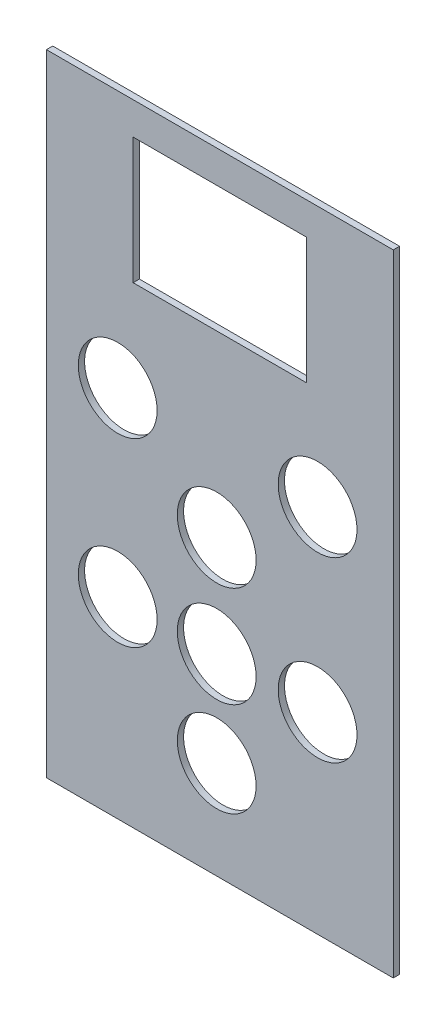
SolidWorks part; units mm, degrees
ref_plane "前视基准面" through (0, 0, 0) normal (0, 0, 1) x (1, 0, 0)
ref_plane "上视基准面" through (0, 0, 0) normal (0, 1, 0) x (1, 0, 0)
ref_plane "右视基准面" through (0, 0, 0) normal (1, 0, 0) x (0, 0, -1)
sketch "草图1" plane through (0, 0, 0) normal (0, 0, 1) x (1, 0, 0)
  line L0 (51.6682, -2.0844) -> (24.1682, -2.0844)
  line L1 (10.4182, 3.0485) -> (65.4182, 3.0485)
  line L2 (10.4182, 3.0485) -> (10.4182, -96.9515)
  line L3 (10.4182, -96.9515) -> (65.4182, -96.9515)
  line L4 (65.4182, 3.0485) -> (65.4182, -96.9515)
  line L5 (51.6682, -2.0844) -> (51.6682, -22.0844)
  line L6 (51.6682, -22.0844) -> (24.1682, -22.0844)
  line L7 (24.1682, -2.0844) -> (24.1682, -22.0844)
  circle A0 centre (37.4182, -81.4515) radius 6.25
  circle A1 centre (37.4182, -66.4515) radius 6.25
  circle A2 centre (21.7182, -66.4515) radius 6.25
  circle A3 centre (53.4182, -66.4515) radius 6.25
  circle A4 centre (37.4182, -50.4515) radius 6.25
  circle A5 centre (53.4182, -38.2515) radius 6.25
  circle A6 centre (21.7182, -37.7515) radius 6.25
  point P24 (38.2018, -66.9216)
  dimension "D3" = 12.5
  dimension "D4" = 12.5
  dimension "D5" = 12.5
  dimension "D6" = 12.5
  dimension "D7" = 12.5
  dimension "D8" = 12.5
  dimension "D9" = 12.5
  dimension "D18" = 27.5
  dimension "D1" = 55
  dimension "D2" = 100
  dimension "D10" = 15
  dimension "D11" = 16
  dimension "D12" = 16
  dimension "D13" = 15.7
  dimension "D14" = 28.2
  dimension "D15" = 28.7
  dimension "D16" = 27
  dimension "D17" = 15.5
  dimension "D19" = 20
  dimension "D20" = 13.75
extrude "凸台-拉伸1" add sketch "草图1" along normal blind 1
